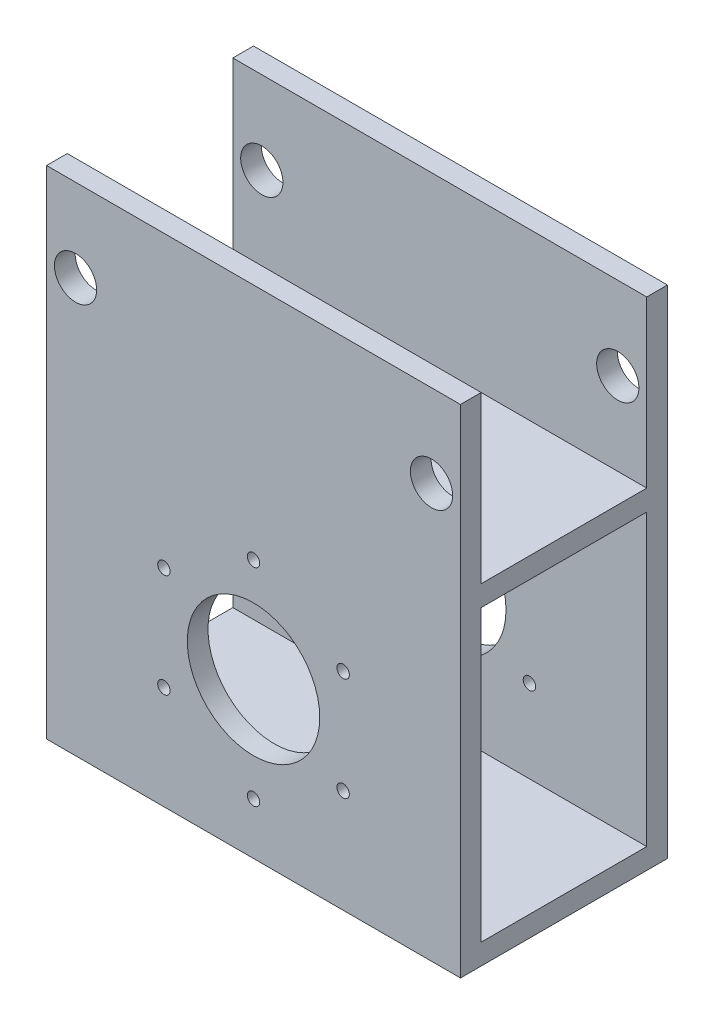
SolidWorks part; units mm, degrees
ref_plane "Front Plane" through (0, 0, 0) normal (0, 0, 1) x (1, 0, 0)
ref_plane "Top Plane" through (0, 0, 0) normal (0, 1, 0) x (1, 0, 0)
ref_plane "Right Plane" through (0, 0, 0) normal (1, 0, 0) x (0, 0, -1)
sketch "Sketch1" plane through (0, 0, 0) normal (0, 0, 1) x (1, 0, 0)
  line L1 (-50, 60) -> (50, 60)
  line L2 (-50, 60) -> (-50, -60)
  line L3 (-50, -60) -> (50, -60)
  line L4 (50, 60) -> (50, -60)
  line L5 (-50, 60) -> (50, -60) construction
  line L6 (-50, -60) -> (50, 60) construction
  point P0 (0, 0)
  dimension "D1" = 100
  dimension "D2" = 120
extrude "Boss-Extrude1" add sketch "Sketch1" along normal blind 5
sketch "Sketch2" plane through (0, 0, 5) normal (0, 0, 1) x (1, 0, 0)
  line L0 (-50, 60) -> (-50, -60) construction
  line L1 (-50, 20) -> (50, 20)
  line L2 (-50, 20) -> (-50, 15)
  line L3 (-50, 15) -> (50, 15)
  line L4 (50, 20) -> (50, 15)
  line L5 (50, -60) -> (50, 60) construction
  line L6 (50, 60) -> (-50, 60) construction
  dimension "D1" = 5
  dimension "D2" = 40
extrude "Boss-Extrude2" add sketch "Sketch2" along normal blind 45
sketch "Sketch3" plane through (0, 20, 0) normal (0, 1, 0) x (1, 0, 0)
  line L0 (50, -50) -> (50, -5) construction
  line L1 (-50, -50) -> (50, -50)
  line L2 (-50, -50) -> (-50, -45)
  line L3 (-50, -45) -> (50, -45)
  line L4 (50, -50) -> (50, -45)
  dimension "D1" = 5
extrude "Boss-Extrude3" add sketch "Sketch3" along normal blind 40 and the other way blind 60
sketch "Sketch6" plane through (0, -40, 0) normal (0, -1, 0) x (1, 0, 0)
  line L1 (-50, 45) -> (50, 45)
  line L2 (-50, 45) -> (-50, 50)
  line L3 (-50, 50) -> (50, 50)
  line L4 (50, 45) -> (50, 50)
  line L5 (-50, 0) -> (50, 0)
  line L6 (-50, 0) -> (-50, 5)
  line L7 (-50, 5) -> (50, 5)
  line L8 (50, 0) -> (50, 5)
extrude "Boss-Extrude4" add sketch "Sketch6" along normal blind 15
sketch "Sketch7" plane through (0, 0, 5) normal (0, 0, 1) x (1, 0, 0)
  line L6 (50, -60) -> (50, 15) construction
  line L7 (-50, -60) -> (50, -60)
  line L8 (-50, -60) -> (-50, -55)
  line L9 (-50, -55) -> (50, -55)
  line L10 (50, -60) -> (50, -55)
  dimension "D1" = 5
extrude "Boss-Extrude5" add sketch "Sketch7" along normal blind 45
sketch "Sketch8" plane through (0, 0, 50) normal (0, 0, 1) x (1, 0, 0)
  line L0 (-50, 15) -> (50, 15) construction
  line L1 (-50, 60) -> (-50, -60) construction
  line L2 (50, -60) -> (50, 60) construction
  line L3 (-50, -60) -> (50, -60) construction
  circle A1 centre (0, -22.5) radius 16
  circle A2 centre (0, -22.5) radius 25 construction
  circle A3 centre (0, 2.5) radius 1.5
  circle A4 centre (21.6506, -10) radius 1.5
  circle A5 centre (21.6506, -35) radius 1.5
  circle A6 centre (0, -47.5) radius 1.5
  circle A7 centre (-21.6506, -35) radius 1.5
  circle A8 centre (-21.6506, -10) radius 1.5
  point P26 (0, -22.5)
  dimension "D1" = 32
  dimension "D4" = 50
  dimension "D2" = 37.5
  dimension "D3" = 75
extrude "Cut-Extrude1" cut sketch "Sketch8" against normal through all
sketch "Sketch9" plane through (0, 0, 50) normal (0, 0, 1) x (1, 0, 0)
  line L0 (0, 60) -> (0, -60) construction
  line L1 (-50, 60) -> (50, 60) construction
  line L2 (-50, -60) -> (50, -60) construction
sketch "Sketch10" plane through (0, 0, 50) normal (0, 0, 1) x (1, 0, 0)
  line L1 (-50, 60) -> (50, 60) construction
  line L3 (0, 60) -> (0, -60) construction
  circle A0 centre (-43, 40) radius 5.1
  circle A1 centre (43, 40) radius 5.1
  point P6 (0, 0)
  dimension "D1" = 10.2
  dimension "D2" = 10.2
  dimension "D3" = 86
  dimension "D4" = 43
  dimension "D5" = 20
  dimension "D6" = 20
extrude "Cut-Extrude2" cut sketch "Sketch10" against normal through all
